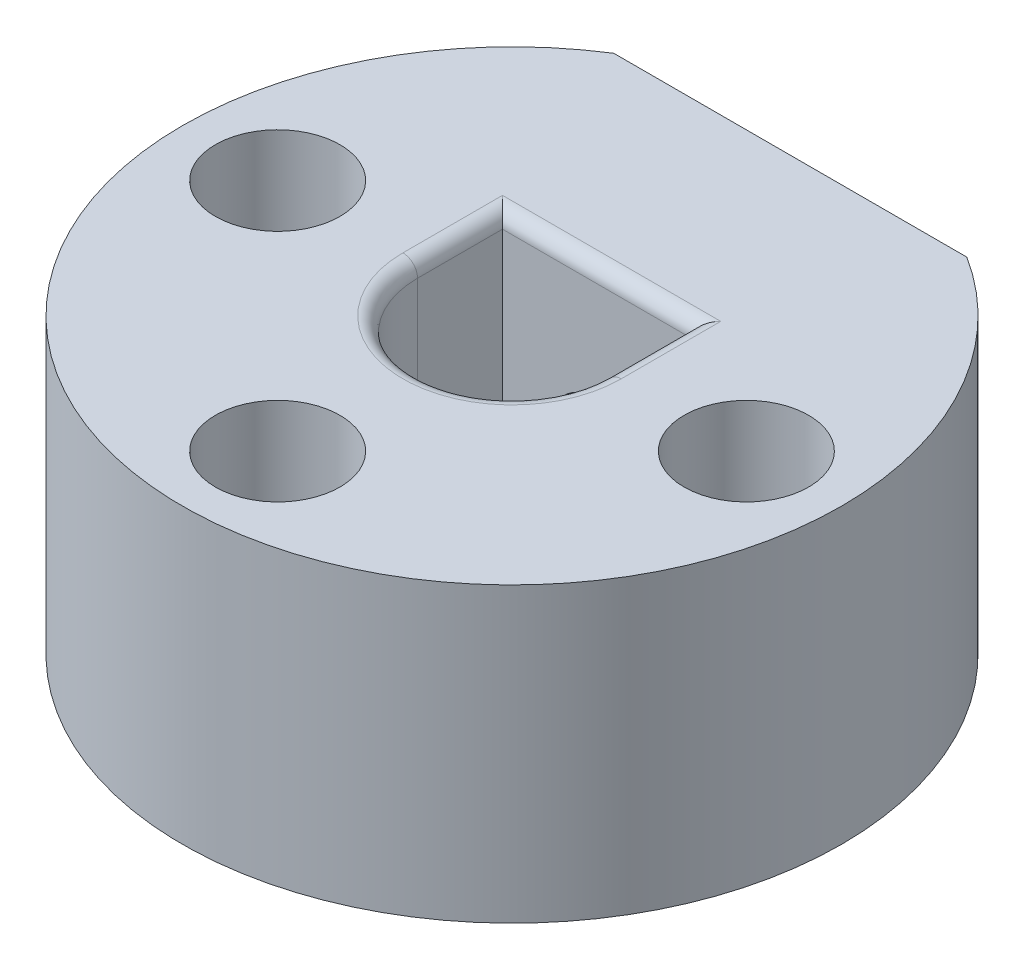
SolidWorks part; units mm, degrees
ref_plane "Plan de face" through (0, 0, 0) normal (0, 0, 1) x (1, 0, 0)
ref_plane "Plan de dessus" through (0, 0, 0) normal (0, 1, 0) x (1, 0, 0)
ref_plane "Plan de droite" through (0, 0, 0) normal (1, 0, 0) x (0, 0, -1)
sketch "Esquisse1" plane through (0, 0, 0) normal (0, 1, 0) x (1, 0, 0)
  line L1 (-3.225, 0) -> (-3.225, 2.9)
  line L2 (3.225, 0) -> (3.225, 2.9)
  line L3 (3.225, 2.9) -> (-3.225, 2.9)
  line L4 (6.026, 9.5) -> (-6.026, 9.5)
  arc A0 (-6.026, 9.5) -> (6.026, 9.5) centre (0, 0) ccw
  arc A1 (-3.225, 0) -> (3.225, 0) centre (0, 0) ccw
  point P10 (0, 2.9)
  dimension "D1" = 22.5
  dimension "D2" = 6.45
  dimension "D3" = 2.9
  dimension "D4" = 9.5
extrude "Boss.-Extru.1" add sketch "Esquisse1" along normal blind 10
hole_wizard "CBORE for M2 SHCS1" positions "Esquisse2" profile "Esquisse3" counterbore size "M2" standard "ANSI Metric" end condition through all
sketch "Esquisse2" plane through (0, 10, 0) normal (0, 1, 0) x (1, 0, 0)
  line L0 (0, 0) -> (6.1221, 0) construction
  line L2 (0, 0) -> (13.3941, 0) construction
  point P0 (8, 0)
  point P28 (-8, 0)
  point P31 (0, 0)
  point P40 (0, -8)
  point P41 (0, 0)
  dimension "D1" = 8
  dimension "D3" = 0
  dimension "D2" = 2
  dimension "D4" = 2
sketch "Esquisse3" plane through (8, 10, 0) normal (1, 0, 0) x (0, 0, 1)
  line L0 (0, 0) -> (0, 10)
  line L1 (0, 10) -> (1.25, 10)
  line L3 (1.25, 10) -> (1.25, 8.5)
  line L4 (1.25, 8.5) -> (2.125, 8.5)
  line L5 (2.125, 8.5) -> (2.125, 0)
  line L7 (2.125, 0) -> (0, 0)
  line L11 (0, -6.35) -> (0, 107.95) construction
  dimension "Diamètre du perçage jusqu'au prochain" = 2.5
  dimension "Profondeur du perçage jusqu'au prochain" = 10
  dimension "Diamètre du chambrage" = 4.25
  dimension "Profondeur du chambrage" = 8.5
fillet "Congé1" radius 0.5 4 edges at (0, 10, 3.225) (-3.225, 10, -1.45) (3.225, 10, -1.45) (0, 10, -2.9)
sketch "Esquisse6" plane through (0, 0, 0) normal (0, 0, 1) x (1, 0, 0)
  line L0 (0, 0) -> (0, 10) construction
  line L1 (11.25, 10) -> (-11.25, 10) construction
  line L2 (11.25, 10) -> (-11.25, 10) construction
  circle A0 centre (0, 4.5) radius 1.6
  dimension "D1" = 3.2
  dimension "D2" = 5.5
extrude "Enlèv. mat.-Extru.1" cut sketch "Esquisse6" against normal through all
sketch "Esquisse7" plane through (0, 0, 0) normal (0, 1, 0) x (1, 0, 0)
  line L1 (-2.925, 4.4) -> (2.925, 4.4)
  line L2 (-2.925, 4.4) -> (-2.925, 6.65)
  line L3 (-2.925, 6.65) -> (2.925, 6.65)
  line L4 (2.925, 4.4) -> (2.925, 6.65)
  line L5 (-2.925, 4.4) -> (2.925, 6.65) construction
  line L6 (-2.925, 6.65) -> (2.925, 4.4) construction
  line L7 (3.225, 2.9) -> (-3.225, 2.9) construction
  point P0 (0, 5.525)
  dimension "D3" = 1.5
  dimension "D1" = 2.25
  dimension "D2" = 5.85
extrude "Enlèv. mat.-Extru.2" cut sketch "Esquisse7" along normal blind 7.25
sketch "Sketch1" plane through (0, 0, 0) normal (0, -1, 0) x (1, 0, 0)
  circle A0 centre (0, 0) radius 4.5
  dimension "D1" = 9
extrude "Cut-Extrude1" cut sketch "Sketch1" against normal blind 3
